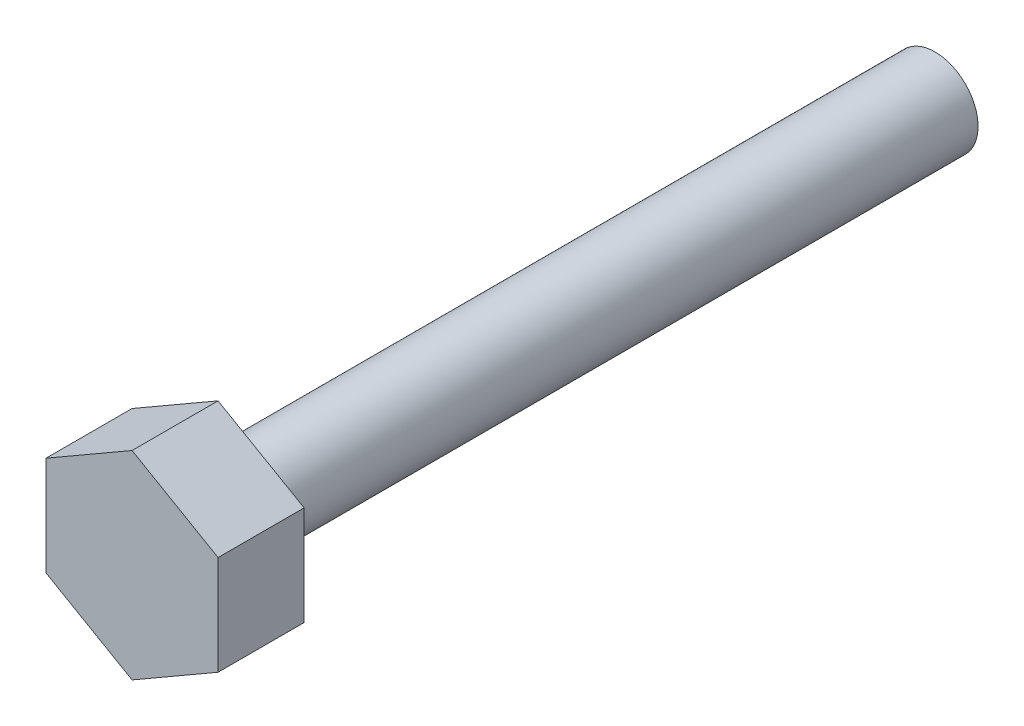
SolidWorks part; units mm, degrees
material "AISI 1020 Steel, Cold Rolled"
ref_plane "Front Plane" through (0, 0, 0) normal (0, 0, 1) x (1, 0, 0)
ref_plane "Top Plane" through (0, 0, 0) normal (0, 1, 0) x (1, 0, 0)
ref_plane "Right Plane" through (0, 0, 0) normal (1, 0, 0) x (0, 0, -1)
sketch "Sketch4" plane through (0, 0, 0) normal (0, 0, 1) x (1, 0, 0)
  line L1 (0, 6.9282) -> (-6, 3.4641)
  line L2 (-6, 3.4641) -> (-6, -3.4641)
  line L3 (-6, -3.4641) -> (0, -6.9282)
  line L4 (0, -6.9282) -> (6, -3.4641)
  line L5 (6, -3.4641) -> (6, 3.4641)
  line L6 (6, 3.4641) -> (0, 6.9282)
  circle A0 centre (0, 0) radius 6 construction
  dimension "D1" = 12
extrude "Boss-Extrude2" add sketch "Sketch4" along normal mid plane 6
sketch "Sketch5" plane through (0, 0, -3) normal (0, 0, -1) x (-1, 0, 0)
  line L6 (0, 6.9282) -> (-6, 3.4641)
  line L7 (-6, 3.4641) -> (-6, -3.4641)
  line L8 (-6, -3.4641) -> (0, -6.9282)
  line L9 (0, -6.9282) -> (6, -3.4641)
  line L10 (6, -3.4641) -> (6, 3.4641)
  line L11 (6, 3.4641) -> (0, 6.9282)
  line L12 (0, 6.9282) -> (-6, 3.4641)
  line L13 (-6, 3.4641) -> (-6, -3.4641)
  line L14 (-6, -3.4641) -> (0, -6.9282)
  line L15 (0, -6.9282) -> (6, -3.4641)
  line L16 (6, -3.4641) -> (6, 3.4641)
  line L17 (6, 3.4641) -> (0, 6.9282)
  circle A0 centre (0, 0) radius 3
  dimension "D2" = 6
  dimension "D1" = 0
extrude "Boss-Extrude3" add sketch "Sketch5" along normal blind 50 contours A0
